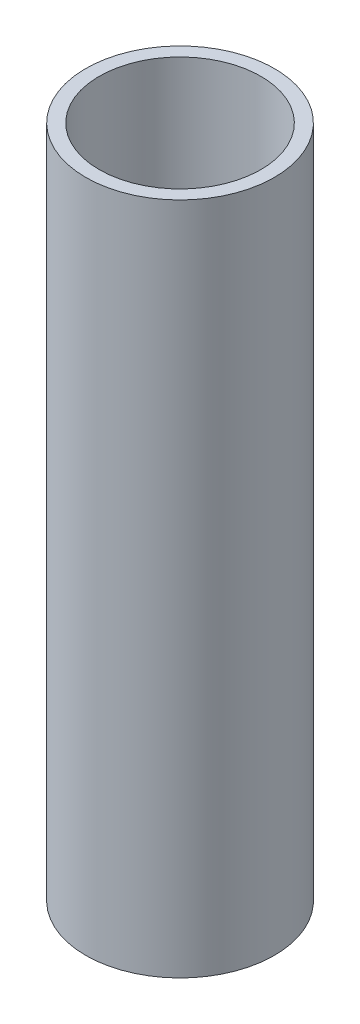
SolidWorks part; units mm, degrees
ref_plane "Front Plane" through (0, 0, 0) normal (0, 0, 1) x (1, 0, 0)
ref_plane "Top Plane" through (0, 0, 0) normal (0, 1, 0) x (1, 0, 0)
ref_plane "Right Plane" through (0, 0, 0) normal (1, 0, 0) x (0, 0, -1)
sketch "Sketch1" plane through (0, 0, 0) normal (0, 1, 0) x (1, 0, 0)
  circle A0 centre (0, 0) radius 7
  circle A1 centre (0, 0) radius 6
  dimension "D1" = 14
  dimension "D2" = 12
extrude "Boss-Extrude1" add sketch "Sketch1" along normal blind 50
